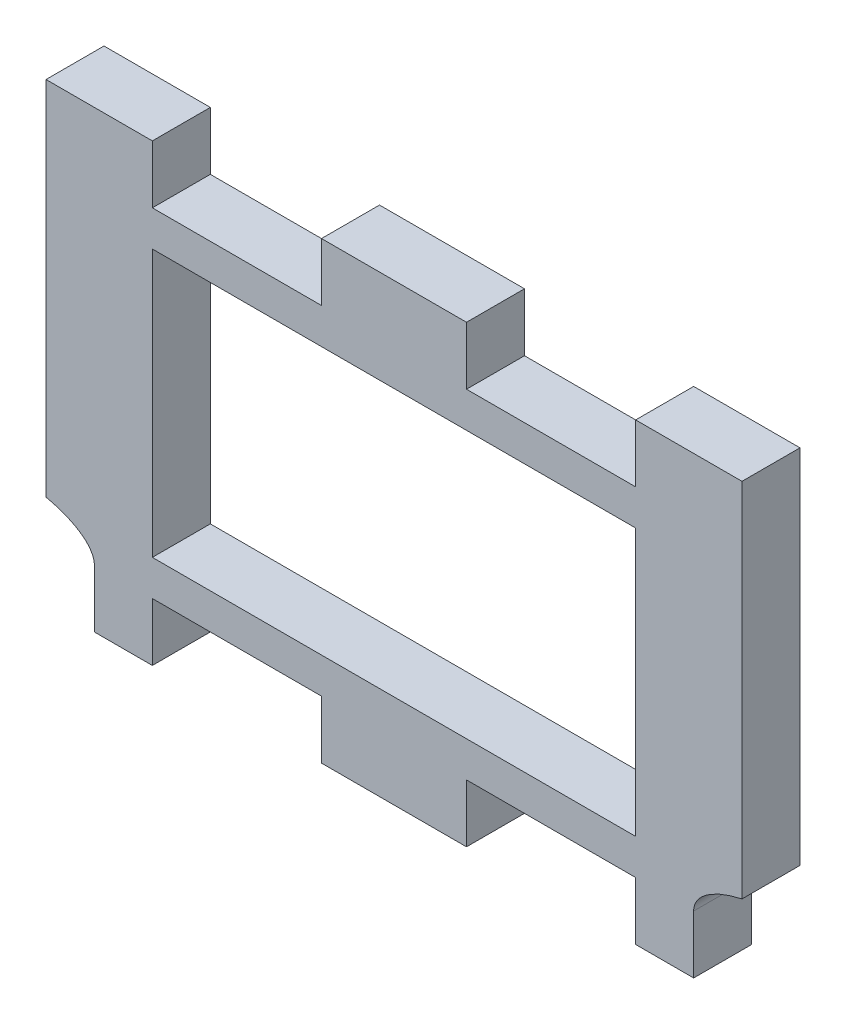
SolidWorks part; units mm, degrees
ref_plane "Front" through (0, 0, 0) normal (0, 0, 1) x (1, 0, 0)
ref_plane "Top" through (0, 0, 0) normal (0, 1, 0) x (1, 0, 0)
ref_plane "Right" through (0, 0, 0) normal (1, 0, 0) x (0, 0, -1)
sketch "Sketch2" plane through (0, 0, 0) normal (0, 0, 1) x (1, 0, 0)
  line L0 (0, 41) -> (-80, 41) construction
  line L1 (0, 0) -> (-80, 0)
  line L2 (0, 0) -> (0, 47)
  line L3 (0, 47) -> (-80, 47)
  line L4 (-80, 0) -> (-80, 47)
  line L5 (0, 6) -> (-80, 6) construction
  line L6 (-4, 0) -> (-4, 47) construction
  line L7 (-15, 0) -> (-15, 47) construction
  line L8 (-76, 0) -> (-76, 47) construction
  line L9 (-65, 0) -> (-65, 47) construction
  line L10 (-47.5, 0) -> (-47.5, 47) construction
  line L11 (-32.5, 0) -> (-32.5, 47) construction
  line L12 (-80, 41) -> (-76, 41)
  line L13 (-76, 41) -> (-76, 47)
  line L14 (-76, 47) -> (-65, 47)
  line L15 (-65, 47) -> (-65, 41)
  line L16 (-65, 41) -> (-47.5, 41)
  line L17 (-47.5, 41) -> (-47.5, 47)
  line L18 (-47.5, 47) -> (-32.5, 47)
  line L19 (-32.5, 47) -> (-32.5, 41)
  line L20 (-32.5, 41) -> (-15, 41)
  line L21 (-15, 41) -> (-15, 47)
  line L22 (-15, 47) -> (-4, 47)
  line L23 (-4, 47) -> (-4, 41)
  line L24 (-4, 41) -> (0, 41)
  line L25 (0, 6) -> (-4, 6)
  line L26 (-4, 6) -> (-4, 0)
  line L27 (-4, 0) -> (-15, 0)
  line L28 (-15, 0) -> (-15, 6)
  line L29 (-15, 6) -> (-32.5, 6)
  line L30 (-32.5, 6) -> (-32.5, 0)
  line L31 (-32.5, 0) -> (-47.5, 0)
  line L32 (-47.5, 0) -> (-47.5, 6)
  line L33 (-47.5, 6) -> (-65, 6)
  line L34 (-65, 6) -> (-65, 0)
  line L35 (-65, 0) -> (-76, 0)
  line L36 (-76, 0) -> (-76, 6)
  line L37 (-76, 6) -> (-80, 6)
  line L38 (-4, 41) -> (-4, 6)
  line L39 (-76, 6) -> (-76, 41)
  line L40 (-9, 6) -> (-9, 0)
  line L41 (-40, 0) -> (-40, 47) construction
  line L42 (-71, 0) -> (-71, 47) construction
  line L43 (-71, 6) -> (-71, 0)
  line L44 (-76, 41) -> (-76, 9.5832)
  line L45 (-4, 41) -> (-4, 9.5832)
  ellipse E0 centre (0, 6) end of major axis (-9, 6) minor radius 4
  ellipse E1 centre (-80, 6) end of major axis (-71, 6) minor radius 4
  dimension "D1" = 47
  dimension "D2" = 80
  dimension "D11" = 6
  dimension "D10" = 32.5
  dimension "D12" = 4
  dimension "D15" = 4
  dimension "D3" = 6
  dimension "D4" = 6
  dimension "D5" = 4
  dimension "D6" = 15
  dimension "D7" = 4
  dimension "D8" = 15
  dimension "D9" = 32.5
  dimension "D13" = 40
  dimension "D14" = 9
extrude "Boss-Extrude1" add sketch "Sketch2" along normal blind 6 contours L37 L36 L1 L34 L33 L32 L30 L29 L28 L26 L25 L2 L24 L23 L3 L21 L20 L19 L17 L16 L15 L13 L12 L4
sketch "Sketch4" plane through (0, 0, 0) normal (0, 0, -1) x (-1, 0, 0)
  line L0 (4, 47) -> (76, 0) construction
  line L1 (76, 47) -> (4, 0) construction
  line L3 (65, 9.6854) -> (15, 9.6854)
  line L4 (65, 9.6854) -> (65, 37.3146)
  line L5 (65, 37.3146) -> (15, 37.3146)
  line L6 (15, 9.6854) -> (15, 37.3146)
  line L7 (65, 9.6854) -> (15, 37.3146) construction
  line L8 (65, 37.3146) -> (15, 9.6854) construction
  line L22 (76, 9.5832) -> (76, 47)
  line L23 (76, 47) -> (65, 47)
  line L24 (65, 47) -> (65, 41)
  line L25 (65, 41) -> (47.5, 41)
  line L26 (47.5, 41) -> (47.5, 47)
  line L27 (47.5, 47) -> (32.5, 47)
  line L28 (32.5, 47) -> (32.5, 41)
  line L29 (32.5, 41) -> (15, 41)
  line L30 (15, 41) -> (15, 47)
  line L31 (15, 47) -> (4, 47)
  line L32 (4, 47) -> (4, 9.5832)
  line L33 (9, 6) -> (9, 0)
  line L34 (9, 0) -> (15, 0)
  line L35 (15, 0) -> (15, 6)
  line L36 (15, 6) -> (32.5, 6)
  line L37 (32.5, 6) -> (32.5, 0)
  line L38 (32.5, 0) -> (47.5, 0)
  line L39 (47.5, 0) -> (47.5, 6)
  line L40 (47.5, 6) -> (65, 6)
  line L41 (65, 6) -> (65, 0)
  line L42 (65, 0) -> (71, 0)
  line L43 (71, 0) -> (71, 6)
  line L44 (76, 9.5832) -> (76, 47)
  line L45 (76, 47) -> (65, 47)
  line L46 (65, 47) -> (65, 41)
  line L47 (65, 41) -> (47.5, 41)
  line L48 (47.5, 41) -> (47.5, 47)
  line L49 (47.5, 47) -> (32.5, 47)
  line L50 (32.5, 47) -> (32.5, 41)
  line L51 (32.5, 41) -> (15, 41)
  line L52 (15, 41) -> (15, 47)
  line L53 (15, 47) -> (4, 47)
  line L54 (4, 47) -> (4, 9.5832)
  line L55 (9, 6) -> (9, 0)
  line L56 (9, 0) -> (15, 0)
  line L57 (15, 0) -> (15, 6)
  line L58 (15, 6) -> (32.5, 6)
  line L59 (32.5, 6) -> (32.5, 0)
  line L60 (32.5, 0) -> (47.5, 0)
  line L61 (47.5, 0) -> (47.5, 6)
  line L62 (47.5, 6) -> (65, 6)
  line L63 (65, 6) -> (65, 0)
  line L64 (65, 0) -> (71, 0)
  line L65 (71, 0) -> (71, 6)
  ellipse E2 centre (80, 6) end of major axis (71, 6) minor radius 4 (76, 9.5832) -> (71, 6) ccw
  ellipse E3 centre (0, 6) end of major axis (9, 6) minor radius 4 (9, 6) -> (4, 9.5832) ccw
  ellipse E4 centre (80, 6) end of major axis (71, 6) minor radius 4 (76, 9.5832) -> (71, 6) ccw
  ellipse E5 centre (0, 6) end of major axis (9, 6) minor radius 4 (9, 6) -> (4, 9.5832) ccw
  point P2 (40, 23.5)
  dimension "D1" = 0
extrude "Cut-Extrude1" cut sketch "Sketch4" against normal through all contours L6 L3 L4 L5
